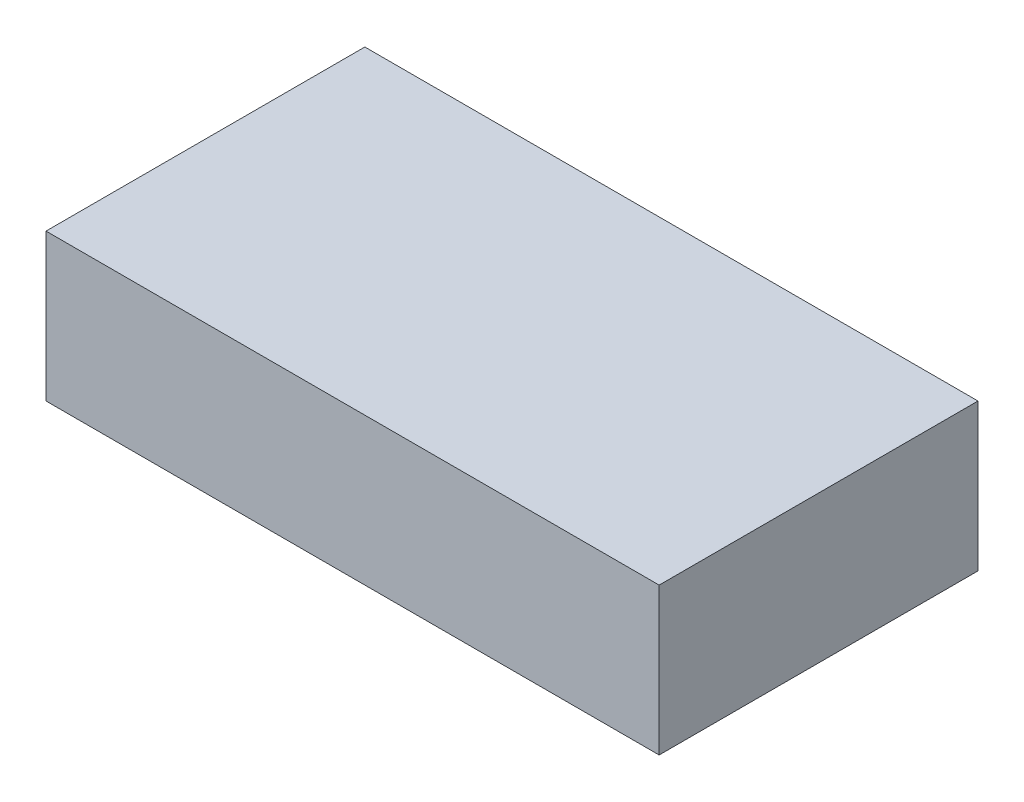
SolidWorks part; units mm, degrees
ref_plane "Front Plane" through (0, 0, 0) normal (0, 0, 1) x (1, 0, 0)
ref_plane "Top Plane" through (0, 0, 0) normal (0, 1, 0) x (1, 0, 0)
ref_plane "Right Plane" through (0, 0, 0) normal (1, 0, 0) x (0, 0, -1)
sketch "Sketch1" plane through (0, 0, 0) normal (0, 1, 0) x (1, 0, 0)
  line L1 (0, 0) -> (25, 0)
  line L2 (0, 0) -> (0, 13)
  line L3 (0, 13) -> (25, 13)
  line L4 (25, 0) -> (25, 13)
  dimension "D1" = 25
  dimension "D2" = 13
extrude "Boss-Extrude1" add sketch "Sketch1" along normal blind 6
